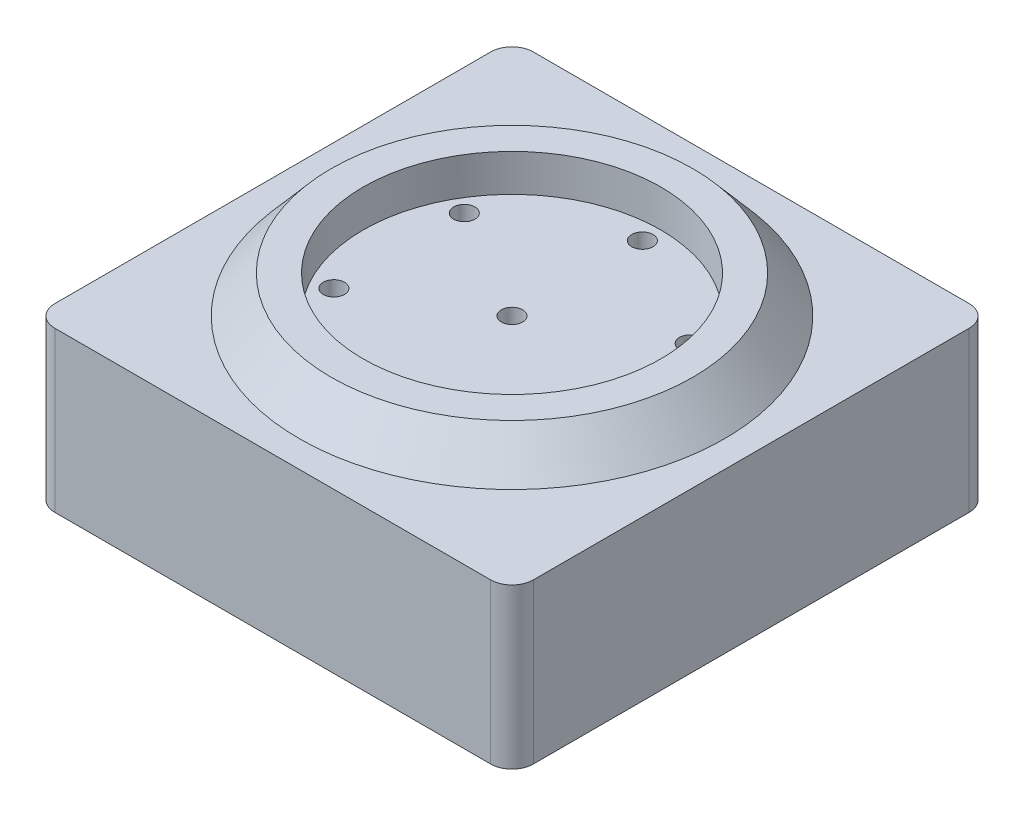
SolidWorks part; units mm, degrees
material "Alloy Steel"
ref_plane "Front Plane" through (0, 0, 0) normal (0, 0, 1) x (1, 0, 0)
ref_plane "Top Plane" through (0, 0, 0) normal (0, 1, 0) x (1, 0, 0)
ref_plane "Right Plane" through (0, 0, 0) normal (1, 0, 0) x (0, 0, -1)
sketch "Turbine Base" plane through (0, 0, 0) normal (0, 1, 0) x (1, 0, 0)
  line L1 (-2050, 2250) -> (2050, 2250)
  line L2 (-2250, 2050) -> (-2250, -2050)
  line L3 (-2050, -2250) -> (2050, -2250)
  line L4 (2250, 2050) -> (2250, -2050)
  line L5 (-2250, 2250) -> (2250, -2250) construction
  line L6 (-2250, -2250) -> (2250, 2250) construction
  arc A0 (2050, 2250) -> (2250, 2050) centre (2050, 2050) cw
  arc A1 (-2250, -2050) -> (-2050, -2250) centre (-2050, -2050) ccw
  arc A2 (-2050, 2250) -> (-2250, 2050) centre (-2050, 2050) ccw
  arc A3 (2050, -2250) -> (2250, -2050) centre (2050, -2050) ccw
  point P0 (0, 0)
  dimension "D3" = 200
  dimension "D1" = 4500
  dimension "D2" = 4500
extrude "Base" add sketch "Turbine Base" along normal blind 1500
sketch "Support " plane through (0, 0, 0) normal (0, 0, 1) x (1, 0, 0)
  line L0 (0, 1850) -> (0, 1500)
  line L1 (0, 1850) -> (1700, 1850)
  line L2 (1700, 1850) -> (2000, 1500)
  line L3 (-2050, 1500) -> (2050, 1500) construction
  line L4 (2000, 1500) -> (0, 1500)
  dimension "D1" = 350
  dimension "D2" = 1700
  dimension "D3" = 2000
revolve "Tower Support projection " add sketch "Support " angle 360 about L0
sketch "external support " plane through (0, 1850, 0) normal (0, 1, 0) x (1, 0, 0)
  line L5 (-1700, 1700) -> (1700, 1700) construction
  line L6 (-1700, 1700) -> (-1700, -1700) construction
  line L7 (-1700, -1700) -> (1700, -1700) construction
  line L8 (1700, 1700) -> (1700, -1700) construction
  line L9 (-1700, 1700) -> (1700, -1700) construction
  line L10 (-1700, -1700) -> (1700, 1700) construction
  circle A4 centre (0, 0) radius 1400
  dimension "D2" = 2800
  dimension "D3" = 3400
extrude "Tower Support " cut sketch "external support " against normal through all
sketch "Base meeting " plane through (0, 0, 0) normal (0, -1, 0) x (1, 0, 0)
  circle A0 centre (0, 0) radius 1400 construction
  circle A1 centre (0, 0) radius 1400
extrude "Tower Base metting point" add sketch "Base meeting " against normal up to surface (1500 mm away) up to face at (-2000, 1500, 0)
sketch "M20 mounting points" plane through (0, 1500, 0) normal (0, 1, 0) x (1, 0, 0)
  circle A0 centre (0, 0) radius 1226.25 construction
  circle A1 centre (0, 1226.25) radius 100
  circle A2 centre (1061.9637, 613.125) radius 100
  circle A3 centre (1061.9637, -613.125) radius 100
  circle A4 centre (0, -1226.25) radius 100
  circle A5 centre (-1061.9637, -613.125) radius 100
  circle A6 centre (-1061.9637, 613.125) radius 100
  point P17 (0, 0)
  dimension "D1" = 2452.5
  dimension "D2" = 200
  dimension "D3" = 6
extrude "Tower Mouning points" cut sketch "M20 mounting points" against normal blind 500
sketch "Gear box shaft connection" plane through (0, 1500, 0) normal (0, 1, 0) x (1, 0, 0)
  circle A0 centre (0, 0) radius 100
  dimension "D1" = 200
extrude "Gear box connecting point " cut sketch "Gear box shaft connection" against normal blind 1000
sketch "Sketch1" plane through (0, 0, 0) normal (0, -1, 0) x (1, 0, 0)
  line L1 (-1750, 1750) -> (1750, 1750)
  line L2 (-1750, 1750) -> (-1750, -1750)
  line L3 (-1750, -1750) -> (1750, -1750)
  line L4 (1750, 1750) -> (1750, -1750)
  line L5 (-1750, 1750) -> (1750, -1750) construction
  line L6 (-1750, -1750) -> (1750, 1750) construction
  point P0 (0, 0)
  dimension "D1" = 3500
  dimension "D2" = 3500
extrude "Base plate" cut sketch "Sketch1" against normal blind 1000 contours L2 L1 L4 L3
sketch "Sketch2" plane through (0, 0, 0) normal (0, -1, 0) x (1, 0, 0)
  line L1 (-2050, 2250) -> (2050, 2250) construction
  line L2 (2050, -2250) -> (-2050, -2250) construction
  line L3 (0, 2250) -> (0, -2250) construction
  line L4 (-2250, -2050) -> (-2250, 2050) construction
  line L5 (-2250, 0) -> (2250, 0) construction
  line L6 (2250, 2050) -> (2250, -2050) construction
  circle A2 centre (2230, -2230) radius 10
  circle A3 centre (2230, 2230) radius 10
  circle A4 centre (-2050, 2050) radius 100
  circle A5 centre (-2050, -2050) radius 100
  circle A6 centre (2050, -2050) radius 100
  circle A7 centre (2050, 2050) radius 100
  point P20 (0, 0)
  dimension "D1" = 200
  dimension "D2" = 200
  dimension "D3" = 200
extrude "Cut-Extrude2" cut sketch "Sketch2" against normal blind 100
